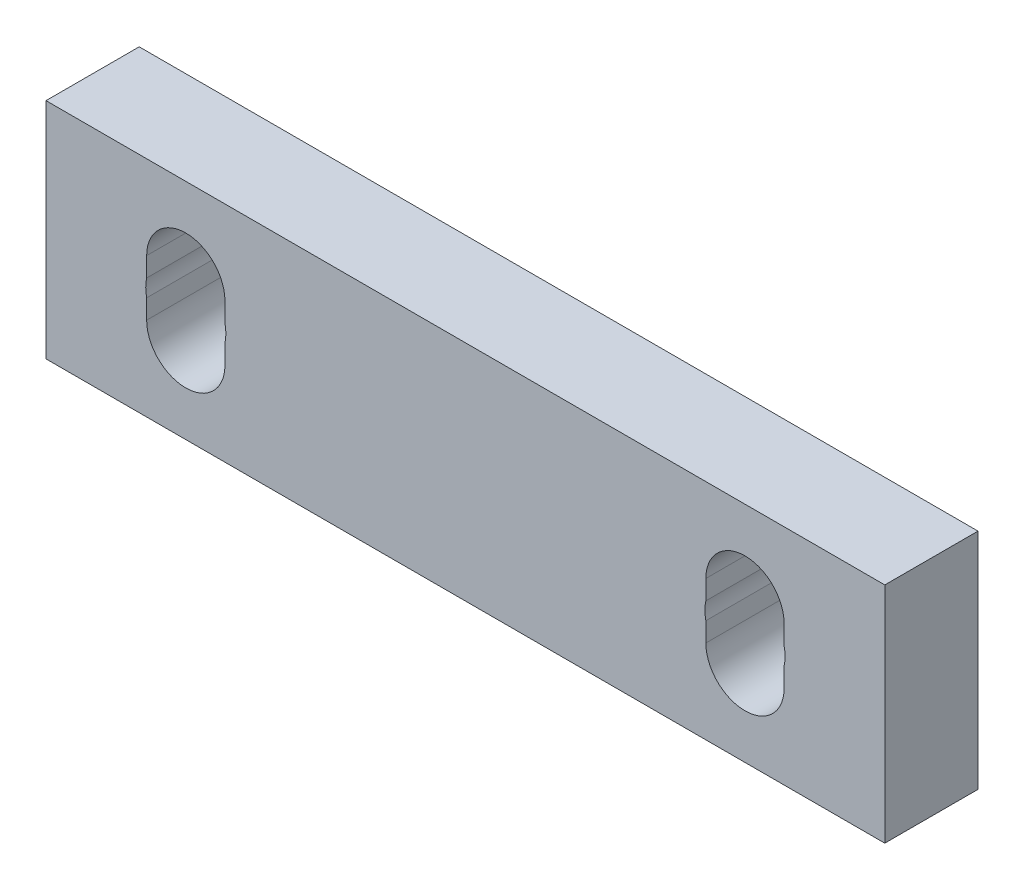
SolidWorks part; units mm, degrees
ref_plane "Front Plane" through (0, 0, 0) normal (0, 0, 1) x (1, 0, 0)
ref_plane "Top Plane" through (0, 0, 0) normal (0, 1, 0) x (1, 0, 0)
ref_plane "Right Plane" through (0, 0, 0) normal (1, 0, 0) x (0, 0, -1)
sketch "Sketch1" plane through (0, 0, 0) normal (0, 0, 1) x (1, 0, 0)
  line L0 (-22.5, 6) -> (22.5, -6) construction
  line L1 (-22.5, 6) -> (22.5, 6)
  line L2 (-22.5, 6) -> (-22.5, -6)
  line L3 (-22.5, -6) -> (22.5, -6)
  line L4 (22.5, 6) -> (22.5, -6)
  line L5 (15, 0) -> (-15, 0) construction
  circle A0 centre (-15, 0) radius 2.15
  circle A1 centre (15, 0) radius 2.15
  dimension "D4" = 4.3
  dimension "D1" = 45
  dimension "D2" = 12
  dimension "D3" = 30
extrude "Boss-Extrude1" add sketch "Sketch1" along normal blind 5
sketch "Sketch2" plane through (0, 0, 5) normal (0, 0, 1) x (1, 0, 0)
  line L0 (-15, 1.5) -> (-15, -1.5) construction
  line L1 (-12.9, 1.5) -> (-12.9, -1.5)
  line L2 (-17.1, 1.5) -> (-17.1, -1.5)
  line L3 (15, -1.5) -> (15, 1.5) construction
  line L4 (12.9, -1.5) -> (12.9, 1.5)
  line L5 (17.1, -1.5) -> (17.1, 1.5)
  arc A0 (-12.9, 1.5) -> (-17.1, 1.5) centre (-15, 1.5) ccw
  arc A1 (-17.1, -1.5) -> (-12.9, -1.5) centre (-15, -1.5) ccw
  arc A2 (12.9, -1.5) -> (17.1, -1.5) centre (15, -1.5) ccw
  arc A3 (17.1, 1.5) -> (12.9, 1.5) centre (15, 1.5) ccw
  circle A4 centre (-15, 0) radius 2.15 construction
  circle A5 centre (15, 0) radius 2.15 construction
  point P2 (-15, 0)
  point P9 (15, 0)
  dimension "D1" = 2.1
  dimension "D2" = 3
extrude "Cut-Extrude1" cut sketch "Sketch2" against normal through all
